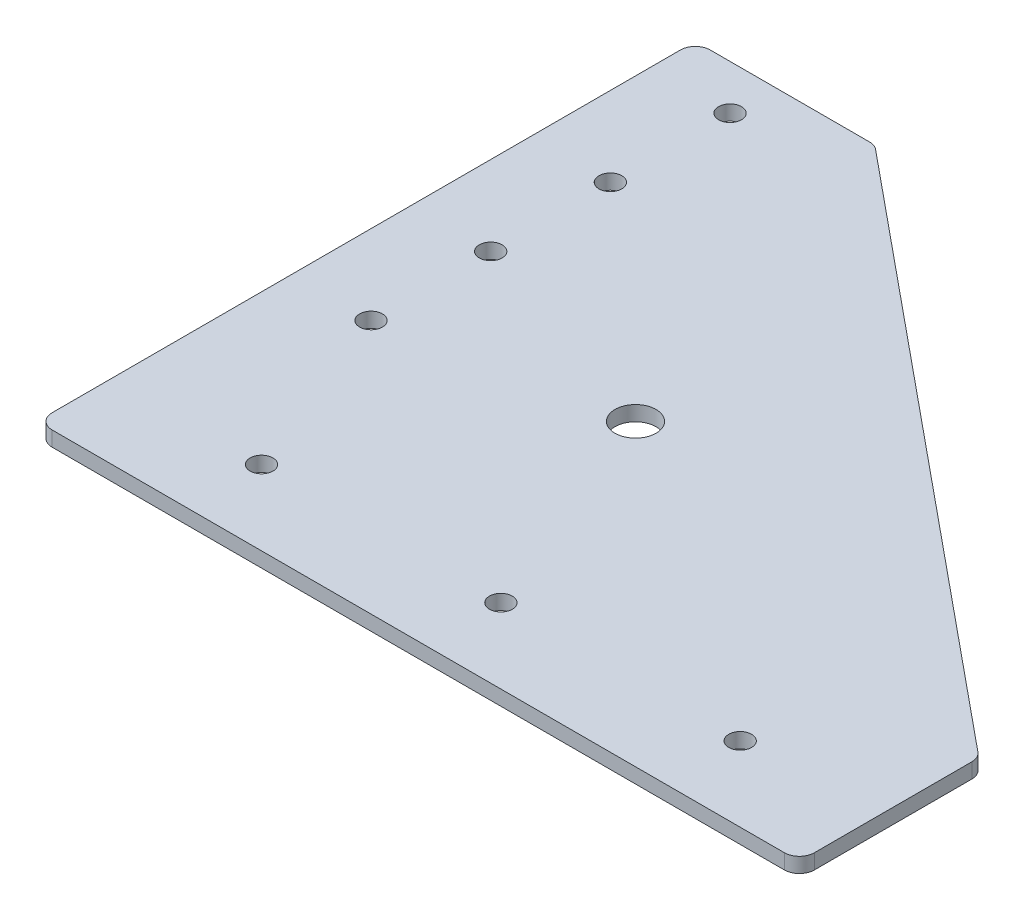
SolidWorks part; units mm, degrees
material "5052-H32"
ref_plane "Front" through (0, 0, 0) normal (0, 0, 1) x (1, 0, 0)
ref_plane "Top" through (0, 0, 0) normal (0, 1, 0) x (1, 0, 0)
ref_plane "Right" through (0, 0, 0) normal (1, 0, 0) x (0, 0, -1)
sketch "Sketch1" plane through (0, 0, 0) normal (0, 1, 0) x (1, 0, 0)
  line L0 (0, 0) -> (0, 139.7)
  line L1 (0, 139.7) -> (38.1, 139.7)
  line L2 (38.1, 139.7) -> (161.7899, 38.1)
  line L3 (0, 0) -> (161.7899, 0)
  line L4 (161.7899, 0) -> (161.7899, 38.1)
  circle A0 centre (31.75, 15.875) radius 2.4257
  circle A1 centre (82.55, 15.875) radius 2.4257
  circle A2 centre (133.35, 15.875) radius 2.4257
  circle A3 centre (16.891, 53.975) radius 2.4257
  circle A4 centre (16.891, 79.375) radius 2.4257
  circle A5 centre (16.891, 104.775) radius 2.4257
  circle A6 centre (16.891, 130.175) radius 2.4257
  dimension "D1" = 4.8514
  dimension "D2" = 139.7
  dimension "D3" = 38.1
  dimension "D4" = 39.4
  dimension "D5" = 15.875
  dimension "D6" = 31.75
  dimension "D8" = 38.1
  dimension "D9" = 50.8
  dimension "D10" = 16.891
  dimension "D11" = 53.975
  dimension "D13" = 25.4
  dimension "D7" = 3
  dimension "D12" = 4
extrude "Boss-Extrude1" add sketch "Sketch1" along normal blind 3.175
fillet "Fillet1" radius 3.175 5 edges at (38.1, 1.5875, -139.7) (0, 1.5875, -139.7) (161.7899, 1.5875, -38.1) (161.7899, 1.5875, 0) (0, 1.5875, 0)
sketch "Sketch2" plane through (0, 3.175, 0) normal (0, 1, 0) x (1, 0, 0)
  line L0 (3.175, 0) -> (158.6149, 0) construction
  line L1 (0, 136.525) -> (0, 3.175) construction
  circle A0 centre (63.5, 63.5) radius 4.3688
  dimension "D1" = 8.7376
  dimension "D2" = 63.5
  dimension "D3" = 63.5
extrude "Cut-Extrude1" cut sketch "Sketch2" against normal through all
